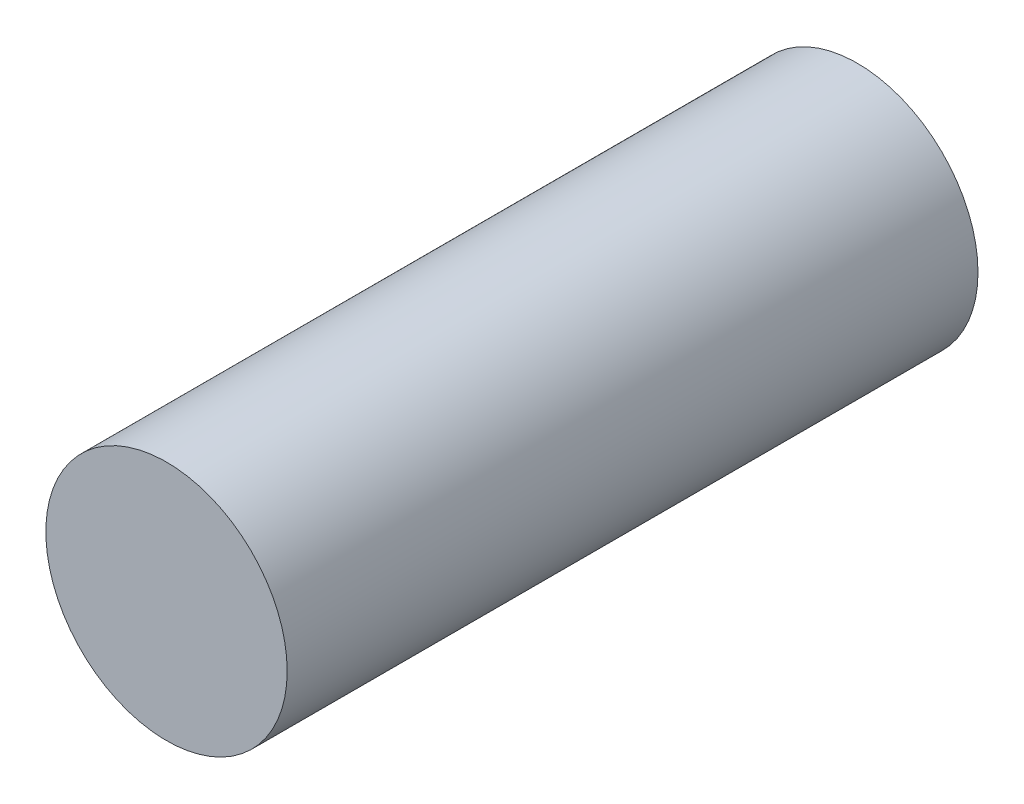
SolidWorks part; units mm, degrees
material "AISI 1020"
ref_plane "Front Plane" through (0, 0, 0) normal (0, 0, 1) x (1, 0, 0)
ref_plane "Top Plane" through (0, 0, 0) normal (0, 1, 0) x (1, 0, 0)
ref_plane "Right Plane" through (0, 0, 0) normal (1, 0, 0) x (0, 0, -1)
sketch "Sketch1" plane through (0, 0, 0) normal (0, 0, 1) x (1, 0, 0)
  circle A0 centre (0, 0) radius 3
  dimension "D1" = 6
extrude "Boss-Extrude1" add sketch "Sketch1" along normal blind 17.175
